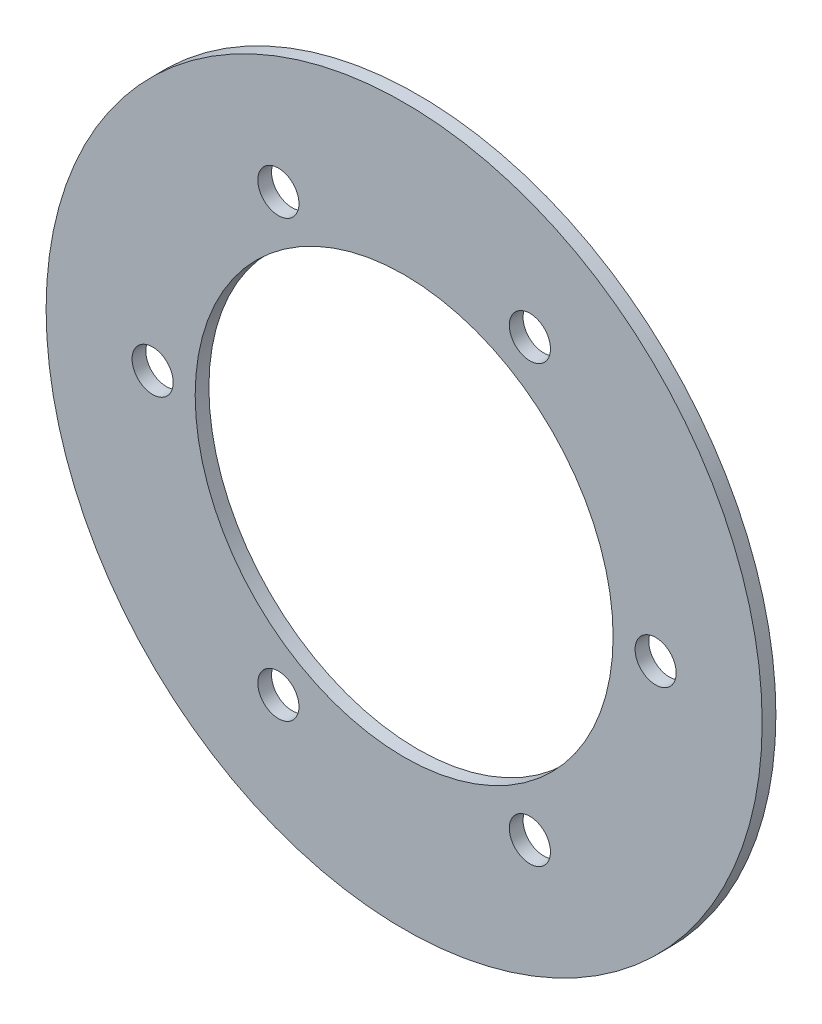
SolidWorks part; units mm, degrees
ref_plane "Ebene vorne" through (0, 0, 0) normal (0, 0, 1) x (1, 0, 0)
ref_plane "Ebene oben" through (0, 0, 0) normal (0, 1, 0) x (1, 0, 0)
ref_plane "Ebene rechts" through (0, 0, 0) normal (1, 0, 0) x (0, 0, -1)
sketch "Skizze1" plane through (0, 0, 0) normal (0, 0, 1) x (1, 0, 0)
  circle A0 centre (0, 0) radius 22.85
  circle A1 centre (0, 0) radius 27.5 construction
  circle A2 centre (0, 0) radius 39.15
extrude "Aufsatz-Linear austragen1" add sketch "Skizze1" along normal blind 1.5
hole_wizard "Durchgangsloch für M41" positions "Skizze2" profile "Skizze3" hole size "M4" standard "DIN" end condition through all
sketch "Skizze2" plane through (0, 0, 1.5) normal (0, 0, 1) x (1, 0, 0)
  circle A0 centre (0, 0) radius 27.5 construction
  point P0 (27.5, 0)
  point P8 (13.75, -23.8157)
  point P9 (-13.75, -23.8157)
  point P10 (-27.5, 0)
  point P11 (-13.75, 23.8157)
  point P12 (13.75, 23.8157)
  dimension "D1" = 6
sketch "Skizze3" plane through (27.5, 0, 1.5) normal (1, 0, 0) x (0, -1, 0)
  line L0 (0, 0) -> (0, 1.5)
  line L1 (0, 1.5) -> (2.25, 1.5)
  line L2 (2.25, 1.5) -> (2.25, 0)
  line L5 (2.25, 0) -> (0, 0)
  line L11 (0, -6.35) -> (0, 107.95) construction
  dimension "Bohrerdurchmesser" = 4.5
  dimension "Bohrungstiefe" = 1.5
